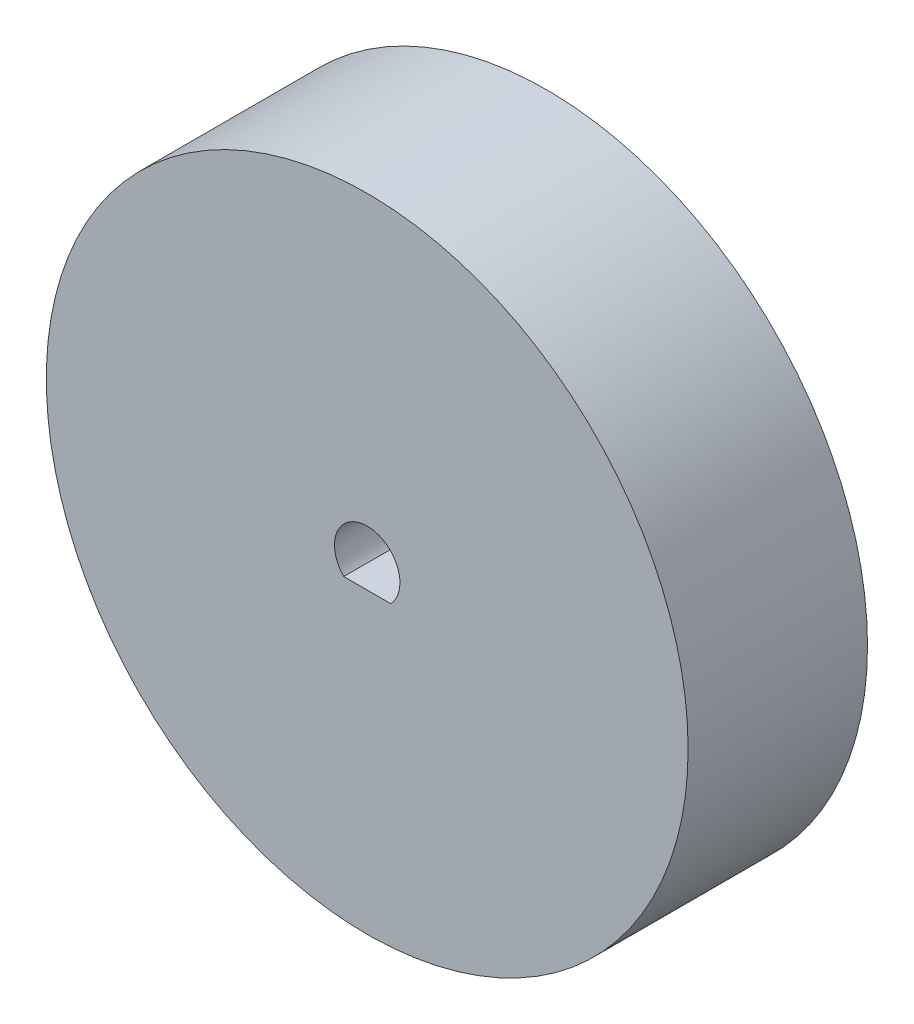
SolidWorks part; units mm, degrees
ref_plane "Front Plane" through (0, 0, 0) normal (0, 0, 1) x (1, 0, 0)
ref_plane "Top Plane" through (0, 0, 0) normal (0, 1, 0) x (1, 0, 0)
ref_plane "Right Plane" through (0, 0, 0) normal (1, 0, 0) x (0, 0, -1)
sketch "Sketch1" plane through (0, 0, 0) normal (0, 0, 1) x (1, 0, 0)
  line L0 (-1.179, -1.14) -> (1.179, -1.14)
  line L1 (-1.118, -1) -> (1.118, -1) construction
  line L2 (20.1816, -47.5311) -> (-30.8001, 10.7607) construction
  circle A0 centre (0, 0) radius 16.1
  arc A1 (1.179, -1.14) -> (-1.179, -1.14) centre (0, 0) ccw
  arc A2 (1.118, -1) -> (-1.118, -1) centre (0, 0) ccw construction
  point P4 (-1.179, -1.14)
  point P5 (1.179, -1.14)
  point P10 (0, 1.5)
  dimension "D1" = 0.14
  dimension "D3" = 1.5
  dimension "D2" = 2.5
extrude "Boss-Extrude1" add sketch "Sketch1" along normal blind 9
